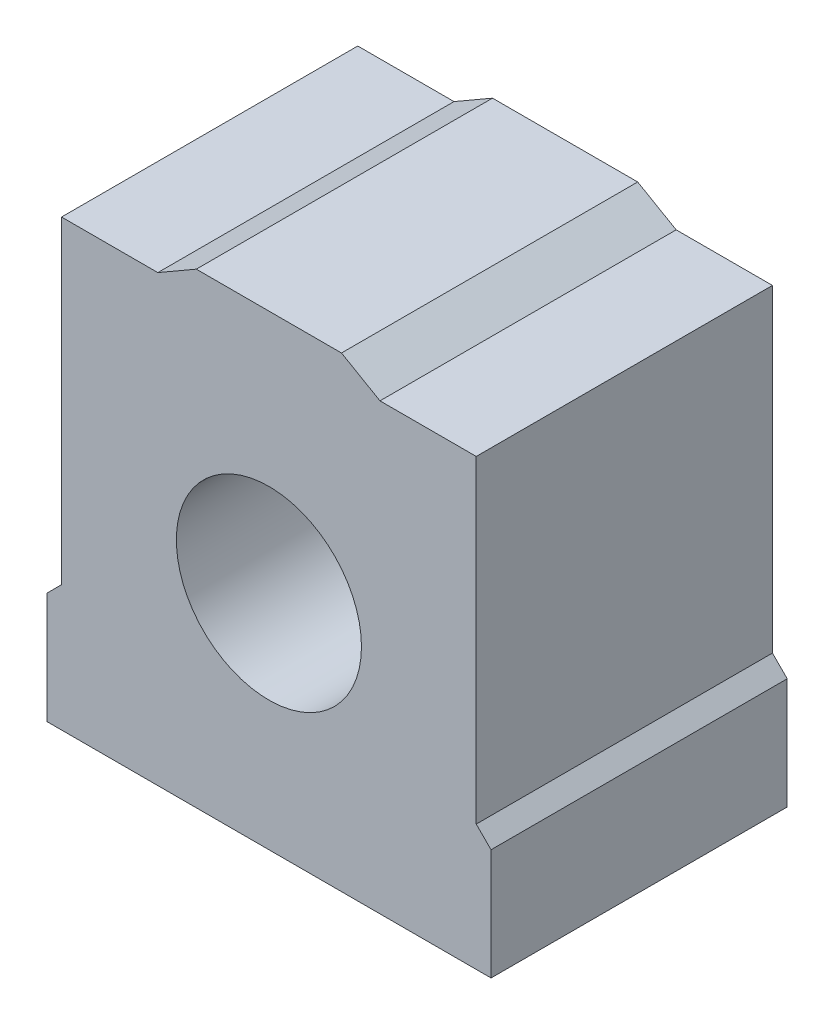
SolidWorks part; units mm, degrees
ref_plane "Alzado" through (0, 0, 0) normal (0, 0, 1) x (1, 0, 0)
ref_plane "Planta" through (0, 0, 0) normal (0, 1, 0) x (1, 0, 0)
ref_plane "Vista lateral" through (0, 0, 0) normal (1, 0, 0) x (0, 0, -1)
sketch "Croquis1" plane through (0, 0, 0) normal (0, 0, 1) x (1, 0, 0)
  line L0 (0, 0) -> (0, 50000) construction
  line L1 (28, 60) -> (15, 60)
  line L2 (30, 15) -> (30, 0)
  line L3 (30, 0) -> (-30, 0)
  line L4 (-30, 15) -> (-30, 0)
  line L7 (-28, 17) -> (-28, 60)
  line L8 (28, 17) -> (28, 60)
  line L9 (-15, 60) -> (-9.8038, 63)
  line L10 (15, 60) -> (9.8038, 63)
  line L11 (-9.8038, 63) -> (9.8038, 63)
  line L12 (-28, 17) -> (-30, 15)
  line L13 (28, 17) -> (30, 15)
  line L14 (-15, 60) -> (-28, 60)
  circle A0 centre (0, 30) radius 12.5
  point P0 (0, 0)
  point P16 (0, 63)
  dimension "D9" = 25
  dimension "D3" = 135
  dimension "D4" = 150
  dimension "D5" = 28
  dimension "D6" = 3
  dimension "D7" = 15
  dimension "D8" = 15
  dimension "D1" = 60
  dimension "D2" = 60
  dimension "D10" = 30
extrude "Saliente-Extruir1" add sketch "Croquis1" along normal mid plane 40
hole_wizard "Taladro roscado 1/4-201" positions "Croquis2" profile "Croquis3" tap size "1/4-20" standard "Ansi Inch"
sketch "Croquis2" plane through (0, 0, 0) normal (0, -1, 0) x (-1, 0, 0)
  line L0 (0, 0) -> (0, -2994.4095) construction
  line L3 (30, 20) -> (-30, 20) construction
  line L4 (30, -20) -> (30, 20) construction
  line L6 (0, 0) -> (50000, 0) construction
  point P0 (20, 10)
  point P22 (20, -10)
  point P24 (-20, -10)
  point P25 (-20, 10)
  dimension "D1" = 10
  dimension "D2" = 10
sketch "Croquis3" plane through (-20, 0, -10) normal (1, 0, 0) x (0, 0, -1)
  line L0 (0, 0) -> (0, 20.5838)
  line L1 (0, 20.5838) -> (2.5527, 19.05)
  line L2 (2.5527, 19.05) -> (2.5527, 0)
  line L5 (2.5527, 0) -> (0, 0)
  line L10 (0, 20.5838) -> (-2.5527, 19.05) construction
  line L11 (0, -6.35) -> (0, 107.95) construction
  dimension "Diámetro de perforador para roscar" = 5.1054
  dimension "Profundidad de perforador para roscar" = 19.05
  dimension "Ángulo de perforador" = 118
equation "\"D5@Croquis1\"=\"D1@Croquis1\"/2-2"
